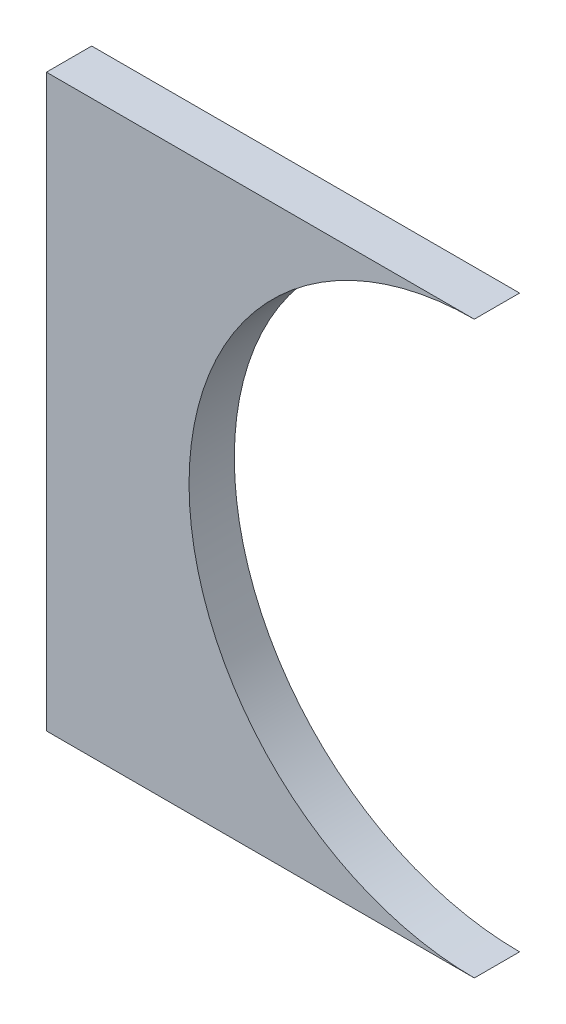
SolidWorks part; units mm, degrees
ref_plane "Front Plane" through (0, 0, 0) normal (0, 0, 1) x (1, 0, 0)
ref_plane "Top Plane" through (0, 0, 0) normal (0, 1, 0) x (1, 0, 0)
ref_plane "Right Plane" through (0, 0, 0) normal (1, 0, 0) x (0, 0, -1)
sketch "Sketch1" plane through (0, 0, 0) normal (0, 0, 1) x (1, 0, 0)
  line L0 (0, 0) -> (30, 0)
  line L1 (0, 0) -> (0, 40)
  line L2 (0, 40) -> (30, 40)
  arc A0 (30, 40) -> (30, 0) centre (30, 20) ccw
  point P7 (29.5522, 0)
  point P8 (10, 20)
  dimension "D1" = 20
  dimension "D2" = 10
extrude "Boss-Extrude1" add sketch "Sketch1" along normal blind 3.175
